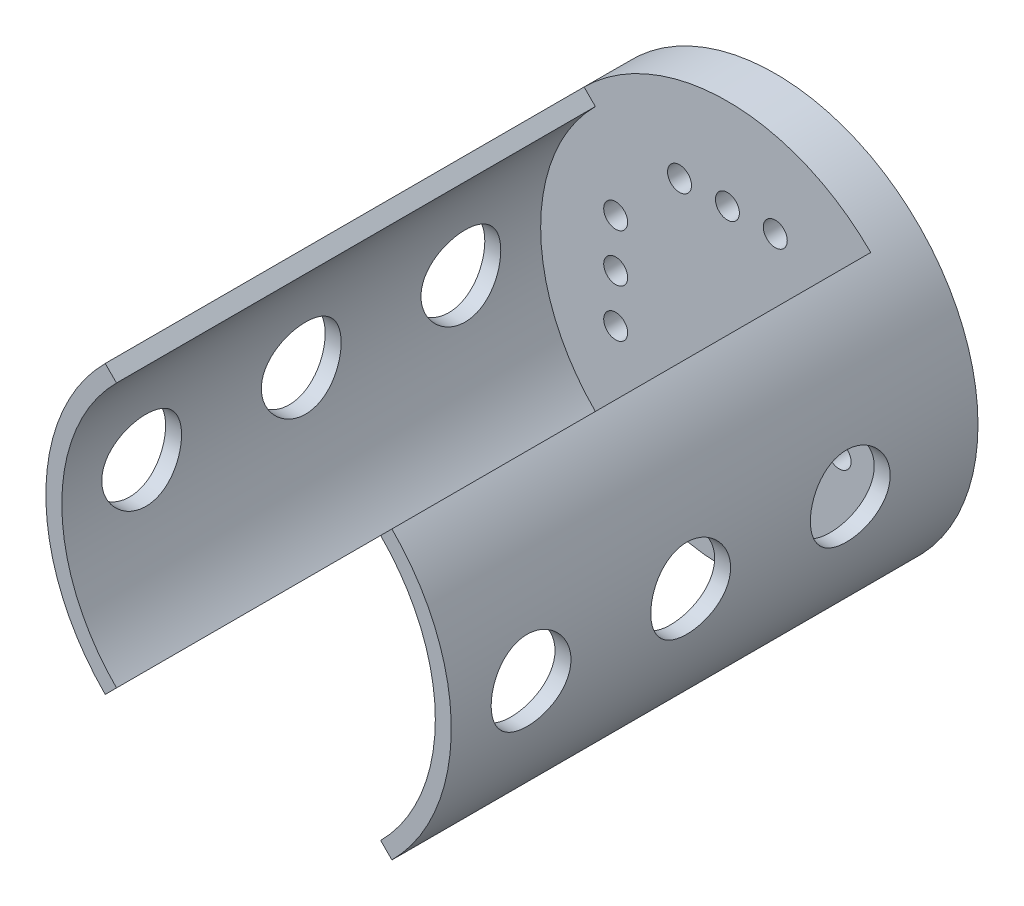
SolidWorks part; units mm, degrees
material "ABS"
ref_plane "Front Plane" through (0, 0, 0) normal (0, 0, 1) x (1, 0, 0)
ref_plane "Top Plane" through (0, 0, 0) normal (0, 1, 0) x (1, 0, 0)
ref_plane "Right Plane" through (0, 0, 0) normal (1, 0, 0) x (0, 0, -1)
sketch "Sketch1" plane through (0, 0, 0) normal (0, 0, 1) x (1, 0, 0)
  circle A0 centre (0, 0) radius 12.7
  dimension "D1" = 25.4
extrude "Boss-Extrude1" add sketch "Sketch1" along normal blind 3
sketch "Sketch2" plane through (0, 0, 3) normal (0, 0, 1) x (1, 0, 0)
  circle A1 centre (0, 7) radius 0.75
  circle A5 centre (-3, 7) radius 0.75
  circle A6 centre (3, 7) radius 0.75
  circle A7 centre (7, -3) radius 0.75
  circle A8 centre (7, 0) radius 0.75
  circle A9 centre (7, 3) radius 0.75
  circle A10 centre (-3, -7) radius 0.75
  circle A11 centre (0, -7) radius 0.75
  circle A12 centre (3, -7) radius 0.75
  circle A13 centre (-7, 3) radius 0.75
  circle A14 centre (-7, 0) radius 0.75
  circle A15 centre (-7, -3) radius 0.75
  dimension "D1" = 7
  dimension "D2" = 1.5
  dimension "D3" = 1.5
  dimension "D4" = 1.5
  dimension "D5" = 3
  dimension "D6" = 3
  dimension "D7" = 4
extrude "Cut-Extrude1" cut sketch "Sketch2" against normal up to surface (3 mm away) up to face at (12.7, 0, 0)
sketch "Sketch3" plane through (0, 0, 3) normal (0, 0, 1) x (1, 0, 0)
  line L2 (-8.9803, 8.9803) -> (-8.2731, 8.2731)
  line L3 (-8.9803, -8.9803) -> (-8.2731, -8.2731)
  line L4 (0, 0) -> (0, 11.1125) construction
  line L5 (8.9803, 8.9803) -> (8.2731, 8.2731)
  line L6 (8.9803, -8.9803) -> (8.2731, -8.2731)
  line L7 (0, 0) -> (-8.9803, 8.9803) construction
  line L8 (0, 0) -> (-8.9803, -8.9803) construction
  arc A0 (-8.9803, -8.9803) -> (-8.9803, 8.9803) centre (0, 0) cw
  arc A2 (-8.2731, 8.2731) -> (-8.2731, -8.2731) centre (0, 0) ccw
  arc A3 (8.9803, -8.9803) -> (8.9803, 8.9803) centre (0, 0) ccw
  arc A4 (8.2731, 8.2731) -> (8.2731, -8.2731) centre (0, 0) cw
  circle A5 centre (0, 0) radius 12.7 construction
  point P4 (0, 0)
  point P5 (0, 0)
  dimension "D1" = 1
  dimension "D2" = 11.7
  dimension "D3" = 1
extrude "Boss-Extrude2" add sketch "Sketch3" along normal blind 30
sketch "Sketch4" plane through (0, 0, 0) normal (1, 0, 0) x (0, 0, -1)
  line L0 (1.65, 0) -> (-1.65, 0) construction
  line L1 (-33, 8.9803) -> (-33, -8.9803) construction
  circle A0 centre (-8, 0) radius 2.5
  circle A1 centre (-18, 0) radius 2.5
  circle A2 centre (-28, 0) radius 2.5
  dimension "D1" = 5
  dimension "D2" = 5
  dimension "D3" = 5
  dimension "D4" = 10
  dimension "D5" = 10
  dimension "D6" = 5
extrude "Cut-Extrude2" cut sketch "Sketch4" against normal up to surface and the other way up to surface up to face at (0, 0, 18) other way up to face at (0, 0, 18)
